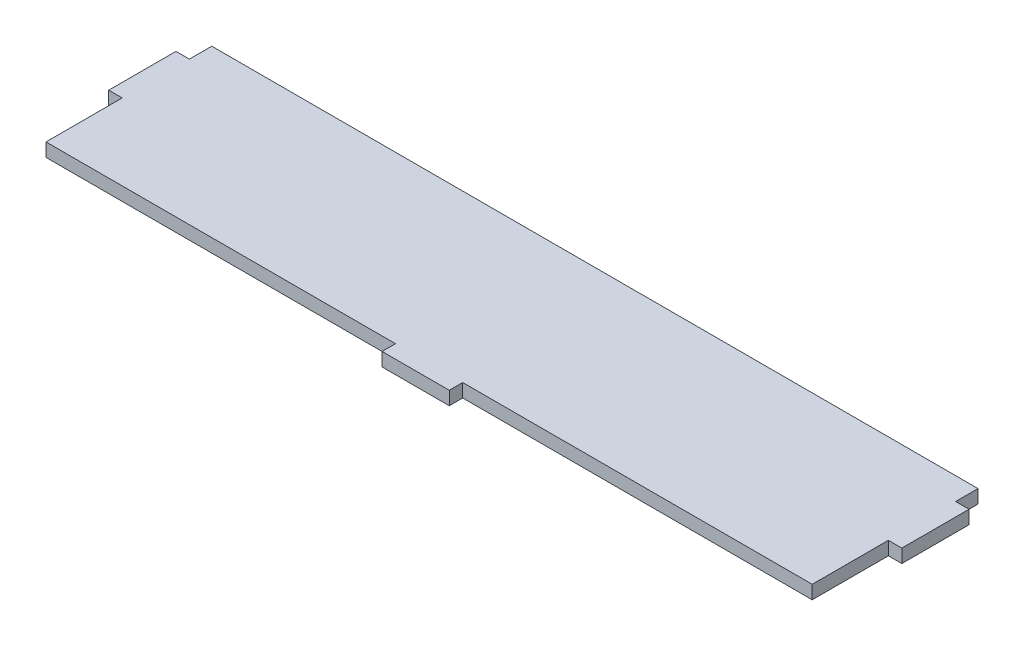
SolidWorks part; units mm, degrees
ref_plane "前视基准面" through (0, 0, 0) normal (0, 0, 1) x (1, 0, 0)
ref_plane "上视基准面" through (0, 0, 0) normal (0, 1, 0) x (1, 0, 0)
ref_plane "右视基准面" through (0, 0, 0) normal (1, 0, 0) x (0, 0, -1)
other "Configuration Table"
sketch "草图1" plane through (0, 0, 0) normal (0, 1, 0) x (1, 0, 0)
  line L0 (0, 35.3659) -> (0, -35.3659) construction
  line L1 (85.5, 20) -> (-85.5, 20)
  line L2 (88.5, 15) -> (88.5, 0)
  line L3 (7.5, -20) -> (-7.5, -20)
  line L4 (-88.5, 15) -> (-88.5, 0)
  line L5 (85.5, 19.322) -> (-88.5, -20) construction
  line L7 (-7.5, -17) -> (-85.5, -17)
  line L8 (-7.5, -20) -> (7.5, -20)
  line L9 (-7.5, -20) -> (-7.5, -17)
  line L11 (7.5, -20) -> (7.5, -17)
  line L12 (7.5, -17) -> (85.5, -17)
  line L13 (-88.5, 15) -> (-88.5, 0) construction
  line L14 (-88.5, -20) -> (88.5, -20) construction
  line L15 (88.5, 15) -> (88.5, 0) construction
  line L16 (85.5, 15) -> (85.5, 20)
  line L17 (-88.5, 15) -> (-85.5, 15)
  line L18 (-88.5, 15) -> (-88.5, 0)
  line L19 (-88.5, 0) -> (-85.5, 0)
  line L21 (88.5, 15) -> (85.5, 15)
  line L22 (88.5, 15) -> (88.5, 0)
  line L23 (88.5, 0) -> (85.5, 0)
  line L25 (85.5, 0) -> (85.5, -17)
  line L26 (88.5, -17) -> (88.5, -20) construction
  line L27 (-85.5, 15) -> (-85.5, 20)
  line L28 (-85.5, 0) -> (-85.5, -17)
  point P0 (0, 0)
  point P2 (0, -20)
  point P28 (0, 0)
  dimension "D1" = 177
  dimension "D2" = 78
  dimension "D3" = 3
  dimension "D4" = 15
  dimension "D5" = 15
  dimension "D6" = 20
  dimension "D7" = 20
  dimension "D8" = 3
  dimension "D9" = 15
  dimension "D10" = 78
extrude "凸台-拉伸1" add sketch "草图1" along normal blind 3 contours L19 L28 L7 L9 L3 L11 L12 L25 L23 L2 L21 L16 L1 L27 L17 L4
